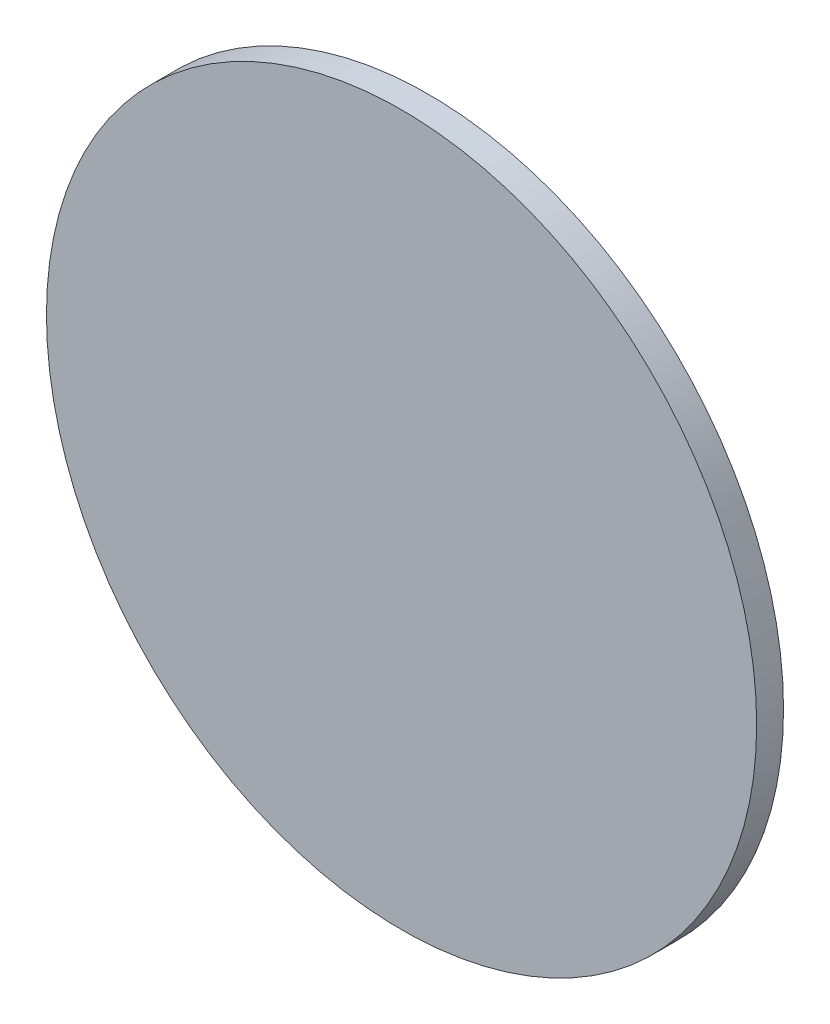
SolidWorks part; units mm, degrees
ref_plane "Front" through (0, 0, 0) normal (0, 0, 1) x (1, 0, 0)
ref_plane "Top" through (0, 0, 0) normal (0, 1, 0) x (1, 0, 0)
ref_plane "Right" through (0, 0, 0) normal (1, 0, 0) x (0, 0, -1)
sketch "Sketch1" plane through (0, 0, 0) normal (0, 0, 1) x (1, 0, 0)
  circle A0 centre (-13.2297, 0) radius 33.5626
extrude "test feature naming" add sketch "Sketch1" along normal blind 2.54
